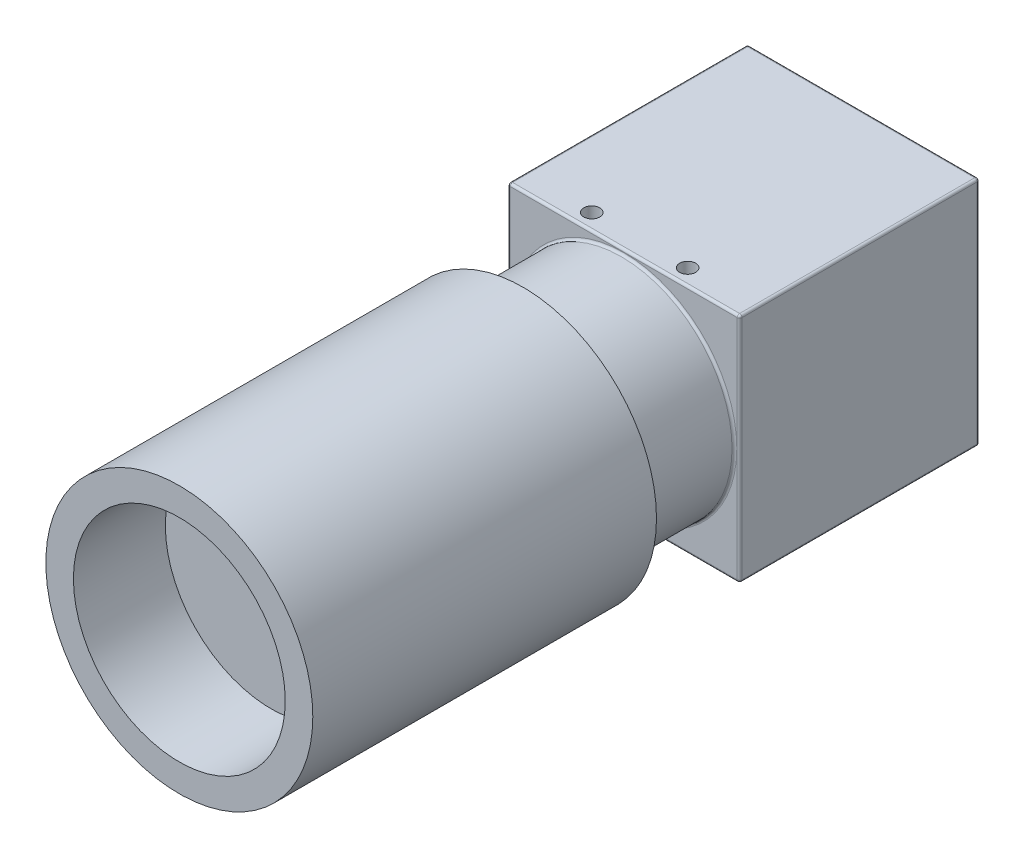
SolidWorks part; units mm, degrees
ref_plane "Front" through (0, 0, 0) normal (0, 0, 1) x (1, 0, 0)
ref_plane "Top" through (0, 0, 0) normal (0, 1, 0) x (1, 0, 0)
ref_plane "Right" through (0, 0, 0) normal (1, 0, 0) x (0, 0, -1)
sketch "Sketch1" plane through (0, 0, 0) normal (0, 0, 1) x (1, 0, 0)
  line L1 (0, 0) -> (29, 0)
  line L2 (0, 0) -> (0, 29)
  line L3 (0, 29) -> (29, 29)
  line L4 (29, 0) -> (29, 29)
  dimension "D1" = 29
  dimension "D2" = 29
extrude "Boss-Extrude1" add sketch "Sketch1" along normal blind 30
sketch "Sketch2" plane through (0, 29, 0) normal (0, 1, 0) x (1, 0, 0)
  line L0 (14.5, -30) -> (14.5, 0) construction
  line L1 (29, -30) -> (0, -30) construction
  line L2 (29, 0) -> (0, 0) construction
  circle A0 centre (8.5, -28) radius 1
  circle A1 centre (20.5, -28) radius 1
  dimension "D1" = 2
  dimension "D2" = 2
  dimension "D3" = 6
extrude "Cut-Extrude1" cut sketch "Sketch2" against normal blind 2.5
sketch "Sketch3" plane through (0, 0, 0) normal (0, -1, 0) x (1, 0, 0)
  line L0 (14.5, 30) -> (14.5, 0) construction
  line L1 (0, 30) -> (29, 30) construction
  line L2 (0, 0) -> (29, 0) construction
  circle A0 centre (24.5, 27) radius 1.5
  circle A1 centre (4.5, 27) radius 1.5
  dimension "D1" = 3
  dimension "D2" = 10
  dimension "D3" = 3
extrude "Cut-Extrude2" cut sketch "Sketch3" against normal blind 2.8
sketch "Sketch4" plane through (0, 0, 0) normal (0, -1, 0) x (1, 0, 0)
  line L0 (14.5, 0) -> (14.5, 11.0338) construction
  line L1 (0, 0) -> (29, 0) construction
  circle A0 centre (14.5, 3.3) radius 1.5
  circle A1 centre (4.5, 27) radius 1.5 construction
  dimension "D1" = 3
  dimension "D2" = 23.7
extrude "Cut-Extrude3" cut sketch "Sketch4" against normal blind 2.5
sketch "Sketch5" plane through (0, 0, 0) normal (0, -1, 0) x (1, 0, 0)
  line L0 (14.5, 30) -> (14.5, 0) construction
  line L1 (0, 30) -> (29, 30) construction
  line L2 (0, 0) -> (29, 0) construction
  line L3 (14.5, 3.3) -> (18.7532, 3.3) construction
  circle A0 centre (20.5, 25.3) radius 1
  circle A1 centre (20.5, 3.3) radius 1
  circle A2 centre (8.5, 3.3) radius 1
  circle A3 centre (8.5, 25.3) radius 1
  dimension "D1" = 2
  dimension "D2" = 6
  dimension "D3" = 2
  dimension "D4" = 22
extrude "Cut-Extrude4" cut sketch "Sketch5" against normal blind 2
sketch "Sketch6" plane through (0, 0, 30) normal (0, 0, 1) x (1, 0, 0)
  line L0 (0, 14.5) -> (29, 14.5) construction
  line L1 (0, 29) -> (0, 0) construction
  line L2 (29, 0) -> (29, 29) construction
  line L3 (14.5, 29) -> (14.5, 0) construction
  line L4 (29, 29) -> (0, 29) construction
  line L5 (0, 0) -> (29, 0) construction
  circle A0 centre (14.5, 14.5) radius 13.85
  dimension "D1" = 27.7
extrude "Boss-Extrude2" add sketch "Sketch6" along normal blind 12.6
sketch "Sketch7" plane through (0, 0, 42.6) normal (0, 0, 1) x (1, 0, 0)
  circle A0 centre (14.5, 14.5) radius 16.7
  dimension "D1" = 33.4
extrude "Boss-Extrude3" add sketch "Sketch7" along normal blind 43
fillet "Fillet1" radius 0.3 13 edges at (14.5, 0, 0) (29, 14.5, 0) (14.5, 29, 0) (0, 14.5, 0) (29, 0, 15) (14.5, 0, 30) (0, 0, 15) (29, 29, 15) (29, 14.5, 30) (0, 14.5, 30) (0, 29, 15) (14.5, 29, 30) (28.35, 14.5, 30)
sketch "Sketch8" plane through (0, 0, 85.6) normal (0, 0, 1) x (1, 0, 0)
  circle A0 centre (14.5, 14.5) radius 13.25
  dimension "D1" = 26.5
extrude "Cut-Extrude5" cut sketch "Sketch8" against normal blind 11.5
